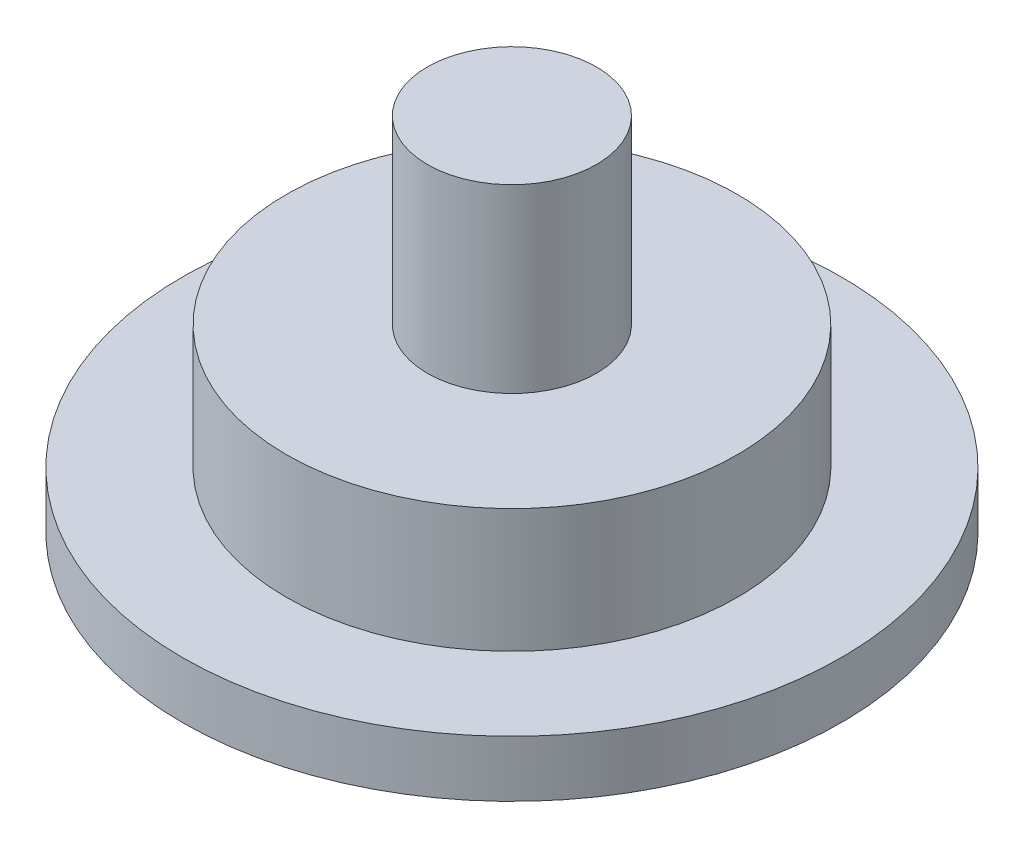
SolidWorks part; units mm, degrees
material "201 Annealed Stainless Steel (SS)"
ref_plane "Front Plane" through (0, 0, 0) normal (0, 0, 1) x (1, 0, 0)
ref_plane "Top Plane" through (0, 0, 0) normal (0, 1, 0) x (1, 0, 0)
ref_plane "Right Plane" through (0, 0, 0) normal (1, 0, 0) x (0, 0, -1)
sketch "Sketch1" plane through (0, 0, 0) normal (0, 1, 0) x (1, 0, 0)
  circle A0 centre (0, 0) radius 7.6
  dimension "D1" = 15.2
extrude "Boss-Extrude1" add sketch "Sketch1" along normal blind 1.3
sketch "Sketch2" plane through (0, 1.3, 0) normal (0, 1, 0) x (1, 0, 0)
  circle A0 centre (0, 0) radius 5.2
  dimension "D1" = 10.4
extrude "Boss-Extrude2" add sketch "Sketch2" along normal blind 2.85
sketch "Sketch3" plane through (0, 4.15, 0) normal (0, 1, 0) x (1, 0, 0)
  circle A0 centre (0, 0) radius 1.95
  dimension "D1" = 3.9
extrude "Boss-Extrude3" add sketch "Sketch3" along normal blind 4.17
sketch "Sketch4" plane through (0, 0, 0) normal (0, -1, 0) x (-1, 0, 0)
  circle A0 centre (0, 0) radius 4.4
  dimension "D1" = 8.8
extrude "Cut-Extrude1" cut sketch "Sketch4" against normal blind 2.76
